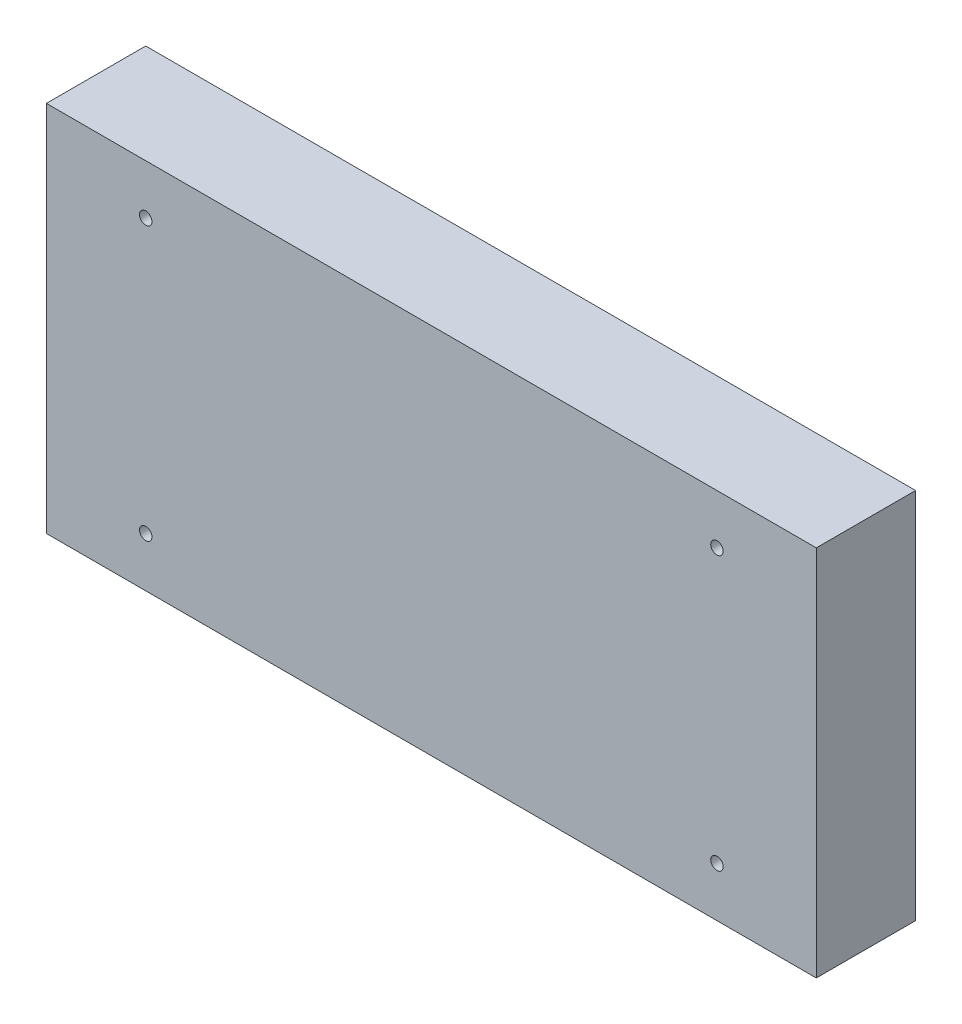
SolidWorks part; units mm, degrees
ref_plane "Plan de face" through (0, 0, 0) normal (0, 0, 1) x (1, 0, 0)
ref_plane "Plan de dessus" through (0, 0, 0) normal (0, 1, 0) x (1, 0, 0)
ref_plane "Plan de droite" through (0, 0, 0) normal (1, 0, 0) x (0, 0, -1)
sketch "Esquisse1" plane through (0, 0, 0) normal (0, 0, 1) x (1, 0, 0)
  line L1 (-36.597, 2.1172) -> (25.403, 2.1172)
  line L2 (-36.597, 2.1172) -> (-36.597, -27.8828)
  line L3 (-36.597, -27.8828) -> (25.403, -27.8828)
  line L4 (25.403, 2.1172) -> (25.403, -27.8828)
extrude "Boss.-Extru.1" add sketch "Esquisse1" along normal blind 8
sketch "Esquisse2" plane through (0, 0, 8) normal (0, 0, 1) x (1, 0, 0)
  line L1 (-36.597, -12.8828) -> (25.403, -12.8828) construction
  line L2 (-36.597, 2.1172) -> (-36.597, -27.8828) construction
  line L3 (25.403, -27.8828) -> (25.403, 2.1172) construction
  line L4 (-5.597, -12.8828) -> (-5.597, 2.1172) construction
  line L6 (25.403, 2.1172) -> (-36.597, 2.1172) construction
  line L7 (-32.597, 2.1172) -> (21.403, 2.1172) construction
  line L8 (-32.597, 2.1172) -> (-32.597, -27.8828) construction
  line L9 (-36.597, -27.8828) -> (25.403, -27.8828) construction
  line L10 (-32.597, -27.8828) -> (21.403, -27.8828) construction
  line L11 (21.403, -27.8828) -> (21.403, 2.1172) construction
  line L12 (-36.597, -1.8828) -> (25.403, -1.8828) construction
  line L13 (-39.3335, -23.8828) -> (27.6046, -23.8828) construction
  line L14 (-28.597, 2.8154) -> (-28.597, -29.2386) construction
  circle A0 centre (-28.597, -1.8828) radius 0.5
  circle A1 centre (-28.597, -23.8828) radius 0.5
  circle A2 centre (17.403, -1.8828) radius 0.5
  circle A3 centre (17.403, -23.8828) radius 0.5
  dimension "D1" = 4
  dimension "D2" = 4
  dimension "D3" = 4
  dimension "D4" = 4
extrude "Enlèv. mat.-Extru.1" cut sketch "Esquisse2" against normal blind 10
